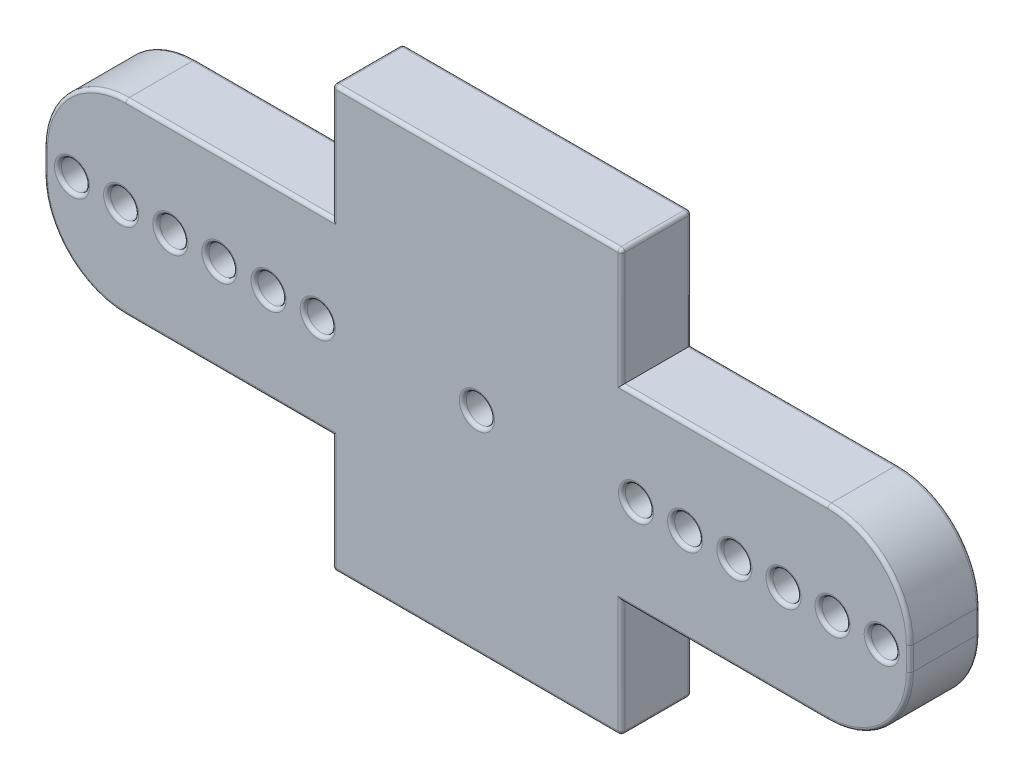
SolidWorks part; units mm, degrees
ref_plane "Front Plane" through (0, 0, 0) normal (0, 0, 1) x (1, 0, 0)
ref_plane "Top Plane" through (0, 0, 0) normal (0, 1, 0) x (1, 0, 0)
ref_plane "Right Plane" through (0, 0, 0) normal (1, 0, 0) x (0, 0, -1)
sketch "Sketch1" plane through (0, 0, 0) normal (0, 0, 1) x (1, 0, 0)
  line L0 (-6.175, 9) -> (6.175, 9)
  line L1 (-18.5, -4) -> (18.5, -4) construction
  line L2 (-18.5, -4) -> (-18.5, 4) construction
  line L3 (-18.5, 4) -> (18.5, 4) construction
  line L4 (18.5, -4) -> (18.5, 4) construction
  line L5 (-18.5, -4) -> (18.5, 4) construction
  line L6 (-18.5, 4) -> (18.5, -4) construction
  line L7 (-6.175, -9) -> (6.175, -9) construction
  line L8 (-6.175, -9) -> (-6.175, 9) construction
  line L9 (-6.175, 9) -> (6.175, 9) construction
  line L10 (6.175, -9) -> (6.175, 9) construction
  line L11 (-6.175, -9) -> (6.175, 9) construction
  line L12 (-6.175, 9) -> (6.175, -9) construction
  line L13 (6.175, 9) -> (6.175, 4)
  line L14 (6.175, 4) -> (15, 4)
  line L15 (18.5, 0.5) -> (18.5, -0.5)
  line L16 (15, -4) -> (6.175, -4)
  line L17 (6.175, -4) -> (6.175, -9)
  line L18 (6.175, -9) -> (-6.175, -9)
  line L19 (-6.175, -9) -> (-6.175, -4)
  line L20 (-6.175, -4) -> (-15, -4)
  line L21 (-18.5, -0.5) -> (-18.5, 0.5)
  line L22 (-15, 4) -> (-6.175, 4)
  line L23 (-6.175, 4) -> (-6.175, 9)
  line L24 (0, 0) -> (0, 4) construction
  circle A6 centre (0, 0) radius 0.6
  circle A13 centre (-17.3, 0) radius 0.6007
  circle A14 centre (-15.2, 0) radius 0.6007
  circle A15 centre (-13.1, 0) radius 0.6007
  circle A16 centre (-11, 0) radius 0.6007
  circle A17 centre (-8.9, 0) radius 0.6007
  circle A18 centre (-6.8, 0) radius 0.6007
  circle A19 centre (6.8, 0) radius 0.6007
  circle A20 centre (8.9, 0) radius 0.6007
  circle A21 centre (11, 0) radius 0.6007
  circle A22 centre (13.1, 0) radius 0.6007
  circle A23 centre (15.2, 0) radius 0.6007
  circle A24 centre (17.3, 0) radius 0.6007
  arc A25 (-18.5, 0.5) -> (-15, 4) centre (-15, 0.5) cw
  arc A26 (18.5, -0.5) -> (15, -4) centre (15, -0.5) cw
  arc A27 (15, 4) -> (18.5, 0.5) centre (15, 0.5) cw
  arc A28 (-15, -4) -> (-18.5, -0.5) centre (-15, -0.5) cw
  point P0 (0, 0)
  point P6 (0, 0)
  dimension "D5" = 1.2014
  dimension "D7" = 6.8
  dimension "D8" = 3.5
  dimension "D9" = 3.5
  dimension "D1" = 12.35
  dimension "D2" = 8
  dimension "D3" = 18
  dimension "D4" = 37
  dimension "D6" = 6
extrude "Boss-Extrude1" add sketch "Sketch1" along normal mid plane 3
fillet "Fillet1" radius 0.15 62 edges at (16.6993, 0, -1.5) (16.6993, 0, 1.5) (14.5993, 0, -1.5) (14.5993, 0, 1.5) (12.4993, 0, -1.5) (12.4993, 0, 1.5) (10.3993, 0, -1.5) (10.3993, 0, 1.5) (8.2993, 0, -1.5) (8.2993, 0, 1.5) (-6.1993, 0, -1.5) (-6.1993, 0, 1.5) (-8.2993, 0, -1.5) (-8.2993, 0, 1.5) (-10.3993, 0, -1.5) (-10.3993, 0, 1.5) (-12.4993, 0, -1.5) (-12.4993, 0, 1.5) (-14.5993, 0, -1.5) (-14.5993, 0, 1.5) (6.1993, 0, -1.5) (6.1993, 0, 1.5) (0.6, 0, -1.5) (0.6, 0, 1.5) (-16.6993, 0, -1.5) (-16.6993, 0, 1.5) (6.175, 6.5, -1.5) (0, 9, -1.5) (-6.175, 6.5, -1.5) (-10.5875, 4, -1.5) (-17.4749, 2.9749, -1.5) (-18.5, 0, -1.5) (-17.4749, -2.9749, -1.5) (-10.5875, -4, -1.5) (-6.175, -6.5, -1.5) (0, -9, -1.5) (6.175, -6.5, -1.5) (10.5875, -4, -1.5) (17.4749, -2.9749, -1.5) (18.5, 0, -1.5) (17.4749, 2.9749, -1.5) (10.5875, 4, -1.5) (6.175, 6.5, 1.5) (0, 9, 1.5) (-6.175, 6.5, 1.5) (-17.4749, 2.9749, 1.5) (-18.5, 0, 1.5) (-17.4749, -2.9749, 1.5) (-10.5875, -4, 1.5) (-6.175, -6.5, 1.5) (0, -9, 1.5) (6.175, -6.5, 1.5) (10.5875, -4, 1.5) (17.4749, -2.9749, 1.5) (18.5, 0, 1.5) (17.4749, 2.9749, 1.5) (10.5875, 4, 1.5) (6.175, -9, 0) (-6.175, -9, 0) (-6.175, 9, 0) (6.175, 9, 0) (-10.5875, 4, 1.5)
